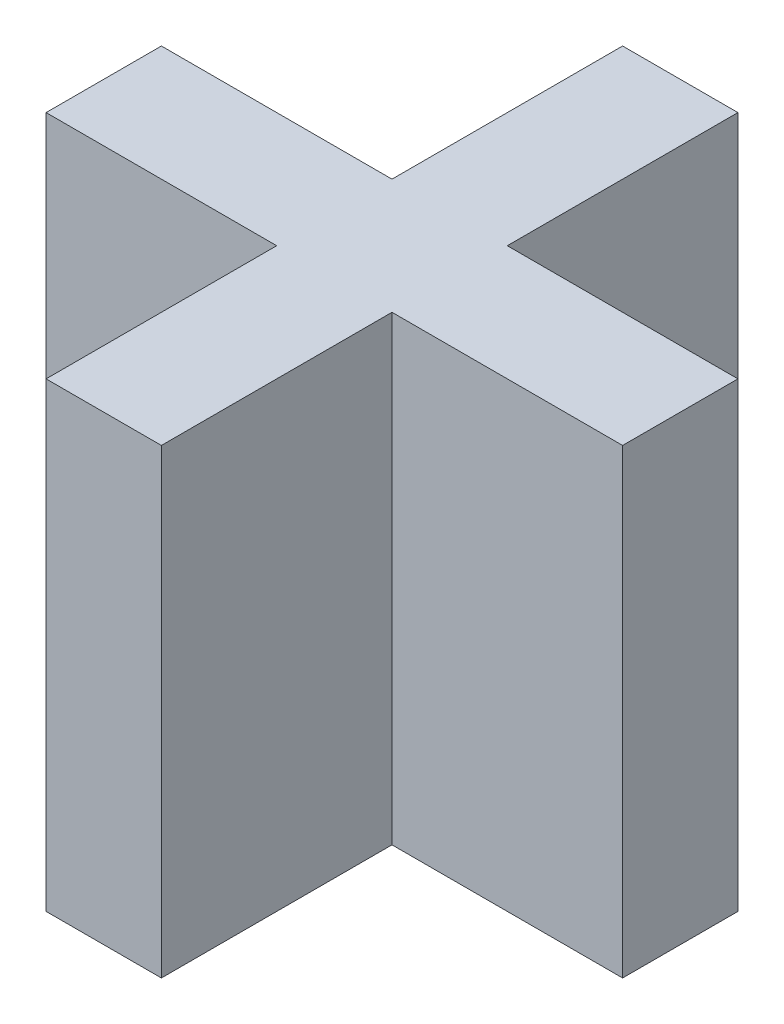
SolidWorks part; units mm, degrees
ref_plane "Alzado" through (0, 0, 0) normal (0, 0, 1) x (1, 0, 0)
ref_plane "Planta" through (0, 0, 0) normal (0, 1, 0) x (1, 0, 0)
ref_plane "Vista lateral" through (0, 0, 0) normal (1, 0, 0) x (0, 0, -1)
sketch "Croquis_cruz" plane through (0, 0, 0) normal (0, 1, 0) x (1, 0, 0)
  line L0 (-62.5, -12.5) -> (-12.5, -12.5)
  line L1 (-12.5, -12.5) -> (-12.5, -62.5)
  line L2 (-12.5, -62.5) -> (12.5, -62.5)
  line L3 (12.5, -62.5) -> (12.5, -12.5)
  line L4 (12.5, -12.5) -> (62.5, -12.5)
  line L5 (62.5, -12.5) -> (62.5, 12.5)
  line L6 (62.5, 12.5) -> (12.5, 12.5)
  line L7 (12.5, 12.5) -> (12.5, 62.5)
  line L8 (12.5, 62.5) -> (-12.5, 62.5)
  line L9 (-12.5, 62.5) -> (-12.5, 12.5)
  line L10 (-12.5, 12.5) -> (-62.5, 12.5)
  line L11 (-62.5, 12.5) -> (-62.5, -12.5)
  dimension "D1" = 50
  dimension "D2" = 75
extrude "Cruz" add sketch "Croquis_cruz" along normal blind 100
sketch "Croquis_agujeros_montaje" plane through (0, 0, 0) normal (0, 1, 0) x (1, 0, 0)
  circle A0 centre (-50, 0) radius 4
  circle A1 centre (0, 0) radius 4
  circle A2 centre (50, 0) radius 4
  dimension "D1" = 8
  dimension "D2" = 50
  dimension "D3" = 100
extrude "Agujero_inserto_M6" cut sketch "Croquis_agujeros_montaje" along normal blind 14
